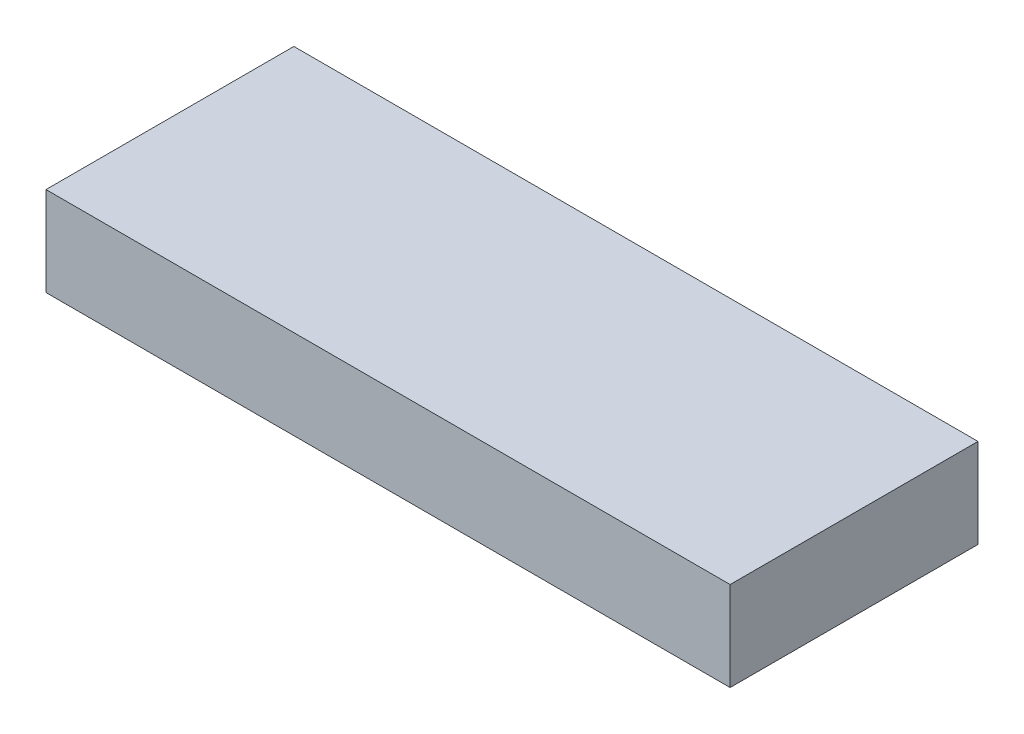
SolidWorks part; units mm, degrees
material "Perspex (TM) GS Acrylic Cast Sheet"
ref_plane "Front Plane" through (0, 0, 0) normal (0, 0, 1) x (1, 0, 0)
ref_plane "Top Plane" through (0, 0, 0) normal (0, 1, 0) x (1, 0, 0)
ref_plane "Right Plane" through (0, 0, 0) normal (1, 0, 0) x (0, 0, -1)
sketch "Sketch1" plane through (0, 0, 0) normal (0, 1, 0) x (1, 0, 0)
  line L1 (-17.25, -6.25) -> (17.25, -6.25)
  line L2 (-17.25, -6.25) -> (-17.25, 6.25)
  line L3 (-17.25, 6.25) -> (17.25, 6.25)
  line L4 (17.25, -6.25) -> (17.25, 6.25)
  line L5 (-17.25, -6.25) -> (17.25, 6.25) construction
  line L6 (-17.25, 6.25) -> (17.25, -6.25) construction
  point P0 (0, 0)
  point P5 (0, 0)
  dimension "D1" = 34.5
  dimension "D2" = 12.5
extrude "Boss-Extrude1" add sketch "Sketch1" along normal blind 4.5
